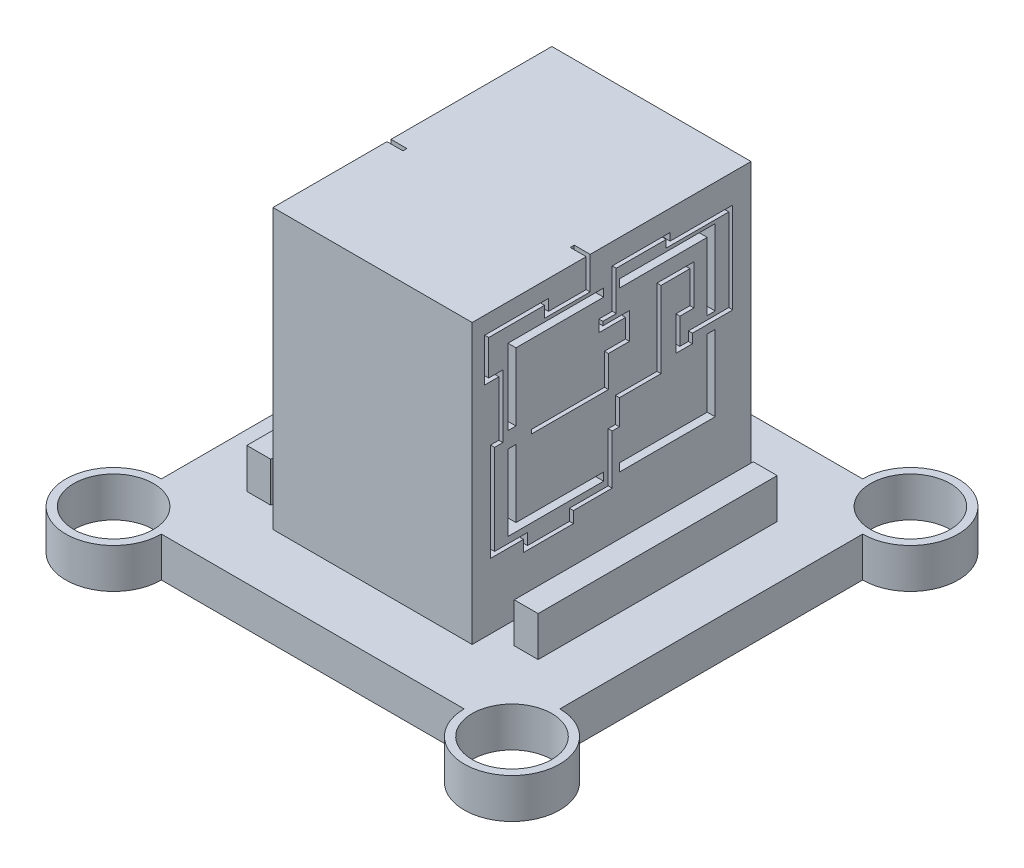
SolidWorks part; units mm, degrees
ref_plane "Front Plane" through (0, 0, 0) normal (0, 0, 1) x (1, 0, 0)
ref_plane "Top Plane" through (0, 0, 0) normal (0, 1, 0) x (1, 0, 0)
ref_plane "Right Plane" through (0, 0, 0) normal (1, 0, 0) x (0, 0, -1)
sketch "Sketch1" plane through (0, 0, 0) normal (0, 1, 0) x (1, 0, 0)
  line L1 (-1.25, -1.25) -> (1.25, -1.25)
  line L2 (-1.25, -1.25) -> (-1.25, 1.25)
  line L3 (-1.25, 1.25) -> (1.25, 1.25)
  line L4 (1.25, -1.25) -> (1.25, 1.25)
  line L5 (-1.25, -1.25) -> (1.25, 1.25) construction
  line L6 (-1.25, 1.25) -> (1.25, -1.25) construction
  circle A0 centre (-1.25, 1.25) radius 0.3
  circle A1 centre (1.25, 1.25) radius 0.3
  circle A2 centre (1.25, -1.25) radius 0.3
  circle A3 centre (-1.25, -1.25) radius 0.3
  point P0 (0, 0)
  dimension "D3" = 0.6
  dimension "D1" = 2.5
  dimension "D2" = 2.5
extrude "Boss-Extrude1" add sketch "Sketch1" along normal blind 0.25 contours A3 L1 A2 L4 A1 L3 A0 L2 | L1 A3 L2 | L2 A3 L1 | L1 A2 L4 | L4 A1 L3 | L3 A0 L2 | L4 A2 L1 | L3 A1 L4 | L2 A0 L3
sketch "Sketch2" plane through (0, 0.25, 0) normal (0, 1, 0) x (1, 0, 0)
  circle A0 centre (-1.25, 1.25) radius 0.25
  circle A1 centre (1.25, 1.25) radius 0.25
  circle A2 centre (1.25, -1.25) radius 0.25
  circle A3 centre (-1.25, -1.25) radius 0.25
  dimension "D1" = 0.5
extrude "Cut-Extrude1" cut sketch "Sketch2" against normal blind 0.25
sketch "Sketch3" plane through (0, 0.25, 0) normal (0, 1, 0) x (1, 0, 0)
  line L0 (-0.914, 0.75) -> (-0.914, -0.75)
  line L1 (-0.914, -0.75) -> (-0.764, -0.75)
  line L2 (-0.764, -0.75) -> (-0.764, 0.75)
  line L3 (-0.764, 0.75) -> (-0.914, 0.75)
  line L4 (0, 0) -> (-1.25, 0) construction
  line L5 (-1.25, -0.95) -> (-1.25, 0.95) construction
  line L6 (0, -0.1375) -> (0, 0.1375) construction
  line L7 (0.914, -0.75) -> (0.764, -0.75)
  line L8 (0.914, 0.75) -> (0.914, -0.75)
  line L9 (0.764, 0.75) -> (0.914, 0.75)
  line L10 (0.764, -0.75) -> (0.764, 0.75)
  point P9 (-0.764, 0)
  dimension "D1" = 0.15
  dimension "D2" = 1.5
extrude "Boss-Extrude2" add sketch "Sketch3" along normal blind 0.25
sketch "Sketch4" plane through (0, 0.25, 0) normal (0, 1, 0) x (1, 0, 0)
  line L1 (-0.625, -0.875) -> (0.625, -0.875)
  line L2 (-0.625, -0.875) -> (-0.625, 0.875)
  line L3 (-0.625, 0.875) -> (0.625, 0.875)
  line L4 (0.625, -0.875) -> (0.625, 0.875)
  line L5 (-0.625, -0.875) -> (0.625, 0.875) construction
  line L6 (-0.625, 0.875) -> (0.625, -0.875) construction
  point P0 (0, 0)
  dimension "D1" = 1.25
  dimension "D2" = 1.75
extrude "Boss-Extrude3" add sketch "Sketch4" along normal blind 1.75
sketch "Sketch5" plane through (0.625, 0, 0) normal (1, 0, 0) x (0, 0, -1)
  line L5 (-0.5938, 0.775) -> (0.5937, 1.725) construction
  line L6 (-0.5937, 1.725) -> (0.5938, 0.775) construction
  line L7 (-0.65, 1.775) -> (-0.05, 1.775)
  line L8 (0.65, 0.725) -> (0.65, 1.2)
  line L9 (-0.65, 0.725) -> (-0.05, 0.725)
  line L10 (-0.65, 0.725) -> (-0.65, 1.2)
  line L11 (-0.6, 1.725) -> (-0.05, 1.725)
  line L12 (0.6, 0.775) -> (0.6, 1.2)
  line L13 (-0.6, 0.775) -> (-0.05, 0.775)
  line L14 (-0.6, 0.775) -> (-0.6, 1.2)
  line L15 (-0.05, 1.775) -> (-0.05, 1.725)
  line L17 (0.05, 1.775) -> (0.05, 1.725)
  line L19 (0.05, 1.775) -> (0.65, 1.775)
  line L23 (0.05, 1.725) -> (0.6, 1.725)
  line L25 (0, 0) -> (0, 2) construction
  line L26 (-0.875, 2) -> (0.875, 2) construction
  line L27 (-0.875, 1.25) -> (0.875, 1.25) construction
  line L28 (-0.875, 2) -> (-0.875, 0.25) construction
  line L29 (0.875, 2) -> (0.875, 0.25) construction
  line L30 (-0.65, 1.3) -> (-0.6, 1.3)
  line L31 (-0.65, 1.2) -> (-0.6, 1.2)
  line L32 (0.6, 1.3) -> (0.65, 1.3)
  line L33 (0.6, 1.2) -> (0.65, 1.2)
  line L34 (-0.05, 0.775) -> (-0.05, 0.725)
  line L35 (0.05, 0.775) -> (0.05, 0.725)
  line L36 (-0.6, 1.3) -> (-0.6, 1.725)
  line L40 (-0.65, 1.3) -> (-0.65, 1.775)
  line L42 (0.05, 0.775) -> (0.6, 0.775)
  line L46 (0.05, 0.725) -> (0.65, 0.725)
  line L48 (0.65, 1.3) -> (0.65, 1.775)
  line L52 (0.6, 1.3) -> (0.6, 1.725)
  point P0 (0, 1.25)
  dimension "D6" = 0.05
  dimension "D7" = 0.05
  dimension "D8" = 0.05
extrude "Cut-Extrude7" cut sketch "Sketch5" against normal blind 1.25
sketch "Sketch8" plane through (0.625, 0, 0) normal (1, 0, 0) x (0, 0, -1)
  line L4 (-0.5034, 1.2328) -> (-0.0447, 1.2328)
  line L5 (-0.0447, 1.2328) -> (-0.0447, 1.4289)
  line L6 (-0.0447, 1.4289) -> (0.0872, 1.4289)
  line L7 (0.0872, 1.4289) -> (0.0872, 1.5466)
  line L8 (0.0872, 1.5466) -> (-0.0797, 1.5466)
  line L9 (-0.0797, 1.5466) -> (-0.0797, 1.6211)
  line L10 (-0.0797, 1.6211) -> (0.0037, 1.6211)
  line L11 (0.0037, 1.6211) -> (0.0037, 1.8679)
  line L12 (0.0037, 1.8679) -> (0.3674, 1.8679)
  line L13 (0.3674, 1.8679) -> (0.3674, 1.8208)
  line L14 (0.3674, 1.8208) -> (0.7602, 1.8208)
  line L15 (0.7602, 1.8208) -> (0.7602, 1.2508)
  line L16 (0.7602, 1.2508) -> (0.5066, 1.2508)
  line L17 (0.5066, 1.2508) -> (0.5066, 1.1932)
  line L18 (0.5066, 1.1932) -> (0.4035, 1.1932)
  line L19 (0.4035, 1.1932) -> (0.4035, 1.4077)
  line L20 (0.4035, 1.4077) -> (0.4921, 1.4077)
  line L21 (0.4921, 1.4077) -> (0.4921, 1.609)
  line L22 (0.4921, 1.609) -> (0.31, 1.609)
  line L23 (0.31, 1.609) -> (0.31, 1.1293)
  line L24 (0.31, 1.1293) -> (0.0492, 1.1293)
  line L25 (0.0492, 1.1293) -> (0.0492, 0.9709)
  line L26 (0.0492, 0.9709) -> (0.0037, 0.9709)
  line L27 (0.0037, 0.9709) -> (0.0037, 0.6603)
  line L28 (0.0037, 0.6603) -> (-0.2394, 0.6603)
  line L29 (-0.2394, 0.6603) -> (-0.2394, 0.589)
  line L30 (-0.2394, 0.589) -> (-0.5529, 0.589)
  line L31 (-0.5529, 0.589) -> (-0.5529, 0.6603)
  line L32 (-0.5529, 0.6603) -> (-0.7592, 0.6603)
  line L33 (-0.7592, 0.6603) -> (-0.7592, 1.276)
  line L36 (-0.7592, 1.276) -> (-0.7072, 1.276)
  line L37 (-0.7072, 1.276) -> (-0.7072, 1.6211)
  line L38 (-0.7072, 1.6211) -> (-0.7961, 1.6211)
  line L39 (-0.7961, 1.6211) -> (-0.7961, 1.8914)
  line L40 (-0.7961, 1.8914) -> (-0.3961, 1.8914)
  line L41 (-0.3961, 1.8914) -> (-0.3961, 1.8208)
  line L42 (-0.3961, 1.8208) -> (-0.1594, 1.8208)
  line L43 (-0.1594, 1.8208) -> (-0.1594, 2)
  line L44 (-0.875, 2) -> (0.875, 2) construction
  line L45 (-0.5034, 1.2078) -> (-0.0197, 1.2078)
  line L46 (-0.0197, 1.2078) -> (-0.0197, 1.4039)
  line L47 (-0.0197, 1.4039) -> (0.1122, 1.4039)
  line L48 (0.1122, 1.4039) -> (0.1122, 1.5716)
  line L49 (0.1122, 1.5716) -> (-0.0547, 1.5716)
  line L50 (-0.0547, 1.5716) -> (-0.0547, 1.5961)
  line L51 (-0.0547, 1.5961) -> (0.0287, 1.5961)
  line L52 (0.0287, 1.5961) -> (0.0287, 1.8429)
  line L53 (0.0287, 1.8429) -> (0.3424, 1.8429)
  line L54 (0.3424, 1.8429) -> (0.3424, 1.7958)
  line L55 (0.3424, 1.7958) -> (0.7352, 1.7958)
  line L56 (0.7352, 1.7958) -> (0.7352, 1.2758)
  line L57 (0.7352, 1.2758) -> (0.4816, 1.2758)
  line L58 (0.4816, 1.2758) -> (0.4816, 1.2182)
  line L59 (0.4816, 1.2182) -> (0.4285, 1.2182)
  line L60 (0.4285, 1.2182) -> (0.4285, 1.3827)
  line L61 (0.4285, 1.3827) -> (0.5171, 1.3827)
  line L62 (0.5171, 1.3827) -> (0.5171, 1.634)
  line L63 (0.5171, 1.634) -> (0.285, 1.634)
  line L64 (0.285, 1.634) -> (0.285, 1.1543)
  line L65 (0.285, 1.1543) -> (0.0242, 1.1543)
  line L66 (0.0242, 1.1543) -> (0.0242, 0.9959)
  line L67 (0.0242, 0.9959) -> (-0.0213, 0.9959)
  line L68 (-0.0213, 0.9959) -> (-0.0213, 0.6853)
  line L69 (-0.0213, 0.6853) -> (-0.2644, 0.6853)
  line L70 (-0.2644, 0.6853) -> (-0.2644, 0.614)
  line L71 (-0.2644, 0.614) -> (-0.5279, 0.614)
  line L72 (-0.5279, 0.614) -> (-0.5279, 0.6853)
  line L73 (-0.5279, 0.6853) -> (-0.7342, 0.6853)
  line L74 (-0.7342, 0.6853) -> (-0.7342, 1.251)
  line L75 (-0.7342, 1.251) -> (-0.6822, 1.251)
  line L76 (-0.6822, 1.251) -> (-0.6822, 1.6461)
  line L77 (-0.6822, 1.6461) -> (-0.7711, 1.6461)
  line L78 (-0.7711, 1.6461) -> (-0.7711, 1.8664)
  line L79 (-0.7711, 1.8664) -> (-0.4211, 1.8664)
  line L80 (-0.4211, 1.8664) -> (-0.4211, 1.7958)
  line L81 (-0.4211, 1.7958) -> (-0.1344, 1.7958)
  line L82 (-0.1344, 1.7958) -> (-0.1344, 2)
  line L83 (-0.5034, 1.2328) -> (-0.5034, 1.2078)
  line L84 (-0.1594, 2) -> (-0.1344, 2)
  dimension "D1" = 0.025
extrude "Cut-Extrude9" cut sketch "Sketch8" against normal blind 0.1
mirror "Mirror2" about plane through (0, 0, 0) normal (1, 0, 0) of "Cut-Extrude9"
scale "Scale1" scale about centroid uniform scaling yes scale factor 5
